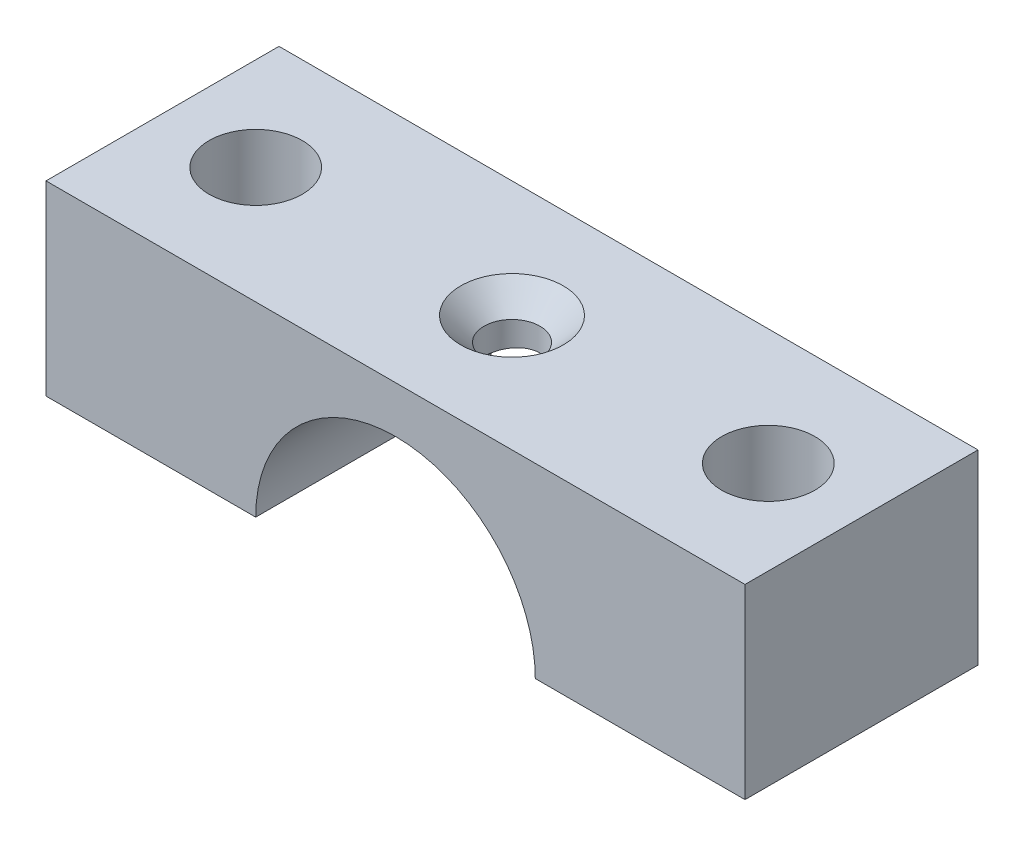
SolidWorks part; units mm, degrees
ref_plane "Front Plane" through (0, 0, 0) normal (0, 0, 1) x (1, 0, 0)
ref_plane "Top Plane" through (0, 0, 0) normal (0, 1, 0) x (1, 0, 0)
ref_plane "Right Plane" through (0, 0, 0) normal (1, 0, 0) x (0, 0, -1)
sketch "Sketch1" plane through (0, 0, 0) normal (0, 0, 1) x (1, 0, 0)
  line L0 (-6, 0) -> (-15, 0)
  line L1 (-15, 0) -> (-15, 8)
  line L2 (-15, 8) -> (15, 8)
  line L3 (15, 8) -> (15, 0)
  line L4 (15, 0) -> (6, 0)
  arc A0 (-6, 0) -> (6, 0) centre (0, 0) cw
  dimension "D5" = 6
  dimension "D1" = 8
  dimension "D2" = 30
  dimension "D3" = 15
  dimension "D4" = 15
extrude "Boss-Extrude1" add sketch "Sketch1" along normal mid plane 10
sketch "Sketch2" plane through (0, 8, 0) normal (0, 1, 0) x (1, 0, 0)
  circle A0 centre (-11, 0) radius 2
  circle A1 centre (11, 0) radius 2
  point P4 (0, 0)
  dimension "D1" = 4
  dimension "D2" = 11
  dimension "D3" = 11
extrude "Cut-Extrude1" cut sketch "Sketch2" against normal through all
hole_wizard "CSK for M2 Flat Head Machine Screw1" positions "Sketch3" profile "Sketch4" countersink size "M2" standard "ANSI Metric" end condition through all
sketch "Sketch3" plane through (0, 8, 0) normal (0, 1, 0) x (1, 0, 0)
  point P0 (0, 0)
sketch "Sketch4" plane through (0, 8, 0) normal (1, 0, 0) x (0, 0, 1)
  line L0 (0, 0) -> (0, 8)
  line L1 (0, 8) -> (1.2, 8)
  line L2 (1.2, 8) -> (1.2, 1)
  line L3 (1.2, 1) -> (2.2, 0)
  line L5 (2.2, 0) -> (0, 0)
  line L6 (-1.2, 1) -> (-2.2, 0) construction
  line L11 (0, -6.35) -> (0, 107.95) construction
  dimension "Thru Hole Dia." = 2.4
  dimension "Thru Hole Depth" = 8
  dimension "Near C'Sink Dia." = 4.4
  dimension "Near C'Sink Angle" = 90
